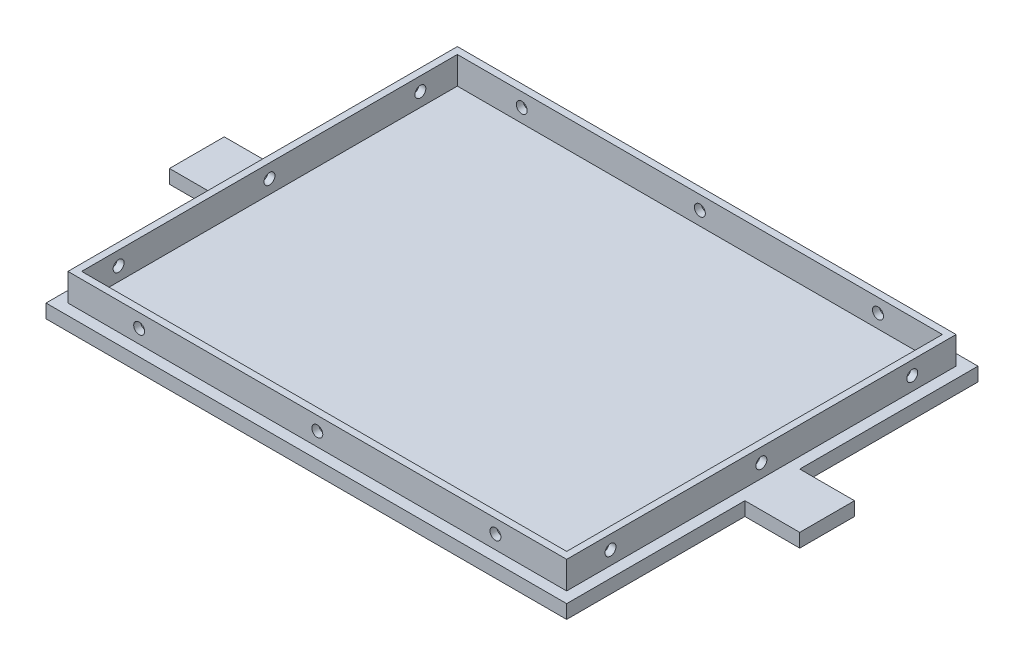
SolidWorks part; units mm, degrees
ref_plane "Front Plane" through (0, 0, 0) normal (0, 0, 1) x (1, 0, 0)
ref_plane "Top Plane" through (0, 0, 0) normal (0, 1, 0) x (1, 0, 0)
ref_plane "Right Plane" through (0, 0, 0) normal (1, 0, 0) x (0, 0, -1)
sketch "Sketch1" plane through (0, 0, 0) normal (0, 1, 0) x (1, 0, 0)
  line L1 (-95, 75.055) -> (95, 75.055)
  line L2 (-95, 75.055) -> (-95, 10)
  line L3 (-95, -75.055) -> (95, -75.055)
  line L4 (95, 75.055) -> (95, 10)
  line L5 (-95, 75.055) -> (95, -75.055) construction
  line L6 (-95, -75.055) -> (95, 75.055) construction
  line L11 (-91, 71.8948) -> (91, -71.8948) construction
  line L12 (-91, -71.8948) -> (91, 71.8948) construction
  line L13 (95, 10) -> (115, 10)
  line L14 (115, 10) -> (115, -10)
  line L15 (115, -10) -> (95, -10)
  line L16 (0, 120.9406) -> (0, 0) construction
  line L18 (-115, 10) -> (-115, -10)
  line L19 (-115, -10) -> (-95, -10)
  line L20 (-95, 10) -> (-115, 10)
  line L21 (95, -10) -> (95, -75.055)
  line L22 (-95, -10) -> (-95, -75.055)
  line L23 (0, -71.8948) -> (0, -75.055) construction
  point P0 (0, 0)
  point P6 (0, 0)
  point P14 (95, 0)
  point P19 (0, 0)
  dimension "D1" = 190
  dimension "D2" = 150.11
  dimension "D4" = 20
  dimension "D5" = 20
extrude "Boss-Extrude1" add sketch "Sketch1" along normal blind 5
sketch "Sketch3" plane through (0, 5, 0) normal (0, 1, 0) x (1, 0, 0)
  line L0 (-95, -75.055) -> (95, -75.055) construction
  line L1 (91, -71.055) -> (-91, -71.055)
  line L2 (91, -71.055) -> (91, 71.055)
  line L3 (91, 71.055) -> (-91, 71.055)
  line L4 (-91, -71.055) -> (-91, 71.055)
  line L5 (95, 75.055) -> (-95, 75.055) construction
  line L6 (-95, 75.055) -> (-95, 10) construction
  line L7 (95, 10) -> (95, 75.055) construction
  line L9 (88.5, -68.555) -> (-88.5, -68.555)
  line L10 (88.5, -68.555) -> (88.5, 68.555)
  line L11 (88.5, 68.555) -> (-88.5, 68.555)
  line L12 (-88.5, -68.555) -> (-88.5, 68.555)
  dimension "D1" = 4
  dimension "D2" = 4
  dimension "D3" = 4
  dimension "D4" = 4
  dimension "D5" = 2.5
  dimension "D6" = 2.5
  dimension "D7" = 2.5
  dimension "D8" = 2.5
extrude "Boss-Extrude2" add sketch "Sketch3" along normal blind 10
sketch "Sketch6" plane through (0, 0, -75.055) normal (0, 0, -1) x (-1, 0, 0)
  line L1 (95, 5) -> (95, 0) construction
  line L2 (-95, 5) -> (-95, 0) construction
  line L3 (-95, 5) -> (-95, 0) construction
  line L4 (-91, 15) -> (91, 15) construction
  circle A0 centre (65, 10) radius 2
  circle A1 centre (0, 10) radius 2
  circle A2 centre (-65, 10) radius 2
  dimension "D4" = 5
  dimension "D1" = 30
  dimension "D2" = 30
  dimension "D3" = 95
  dimension "D5" = 5
  dimension "D6" = 5
extrude "Cut-Extrude3" cut sketch "Sketch6" against normal blind 211
sketch "Sketch8" plane through (-95, 0, 0) normal (-1, 0, 0) x (0, 0, 1)
  line L0 (75.055, 5) -> (75.055, 0) construction
  line L1 (-75.055, 5) -> (-75.055, 0) construction
  line L2 (-71.055, 15) -> (71.055, 15) construction
  circle A0 centre (55.055, 10) radius 2
  circle A1 centre (0, 10) radius 2
  circle A2 centre (-55.055, 10) radius 2
  point P8 (0, 0)
  point P11 (0, 0)
  dimension "D4" = 5
  dimension "D1" = 20
  dimension "D2" = 20
  dimension "D3" = 75.055
  dimension "D5" = 5
  dimension "D6" = 5
extrude "Cut-Extrude4" cut sketch "Sketch8" against normal blind 211
